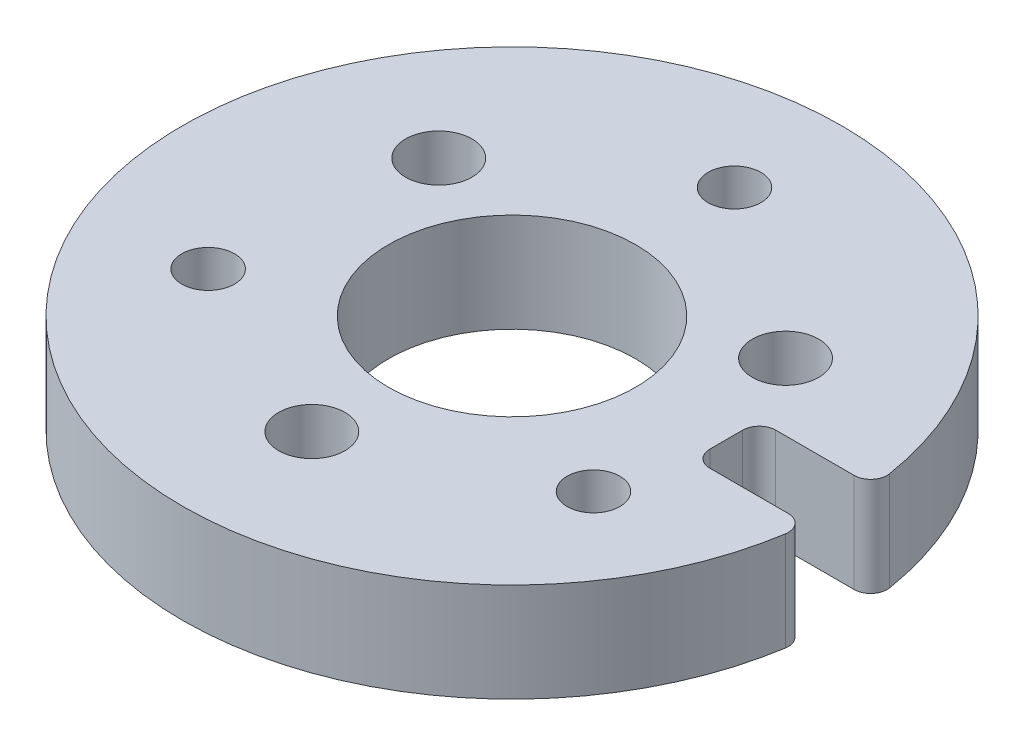
SolidWorks part; units mm, degrees
material "6061 合金"
ref_plane "Front Plane" through (0, 0, 0) normal (0, 0, 1) x (1, 0, 0)
ref_plane "Top Plane" through (0, 0, 0) normal (0, 1, 0) x (1, 0, 0)
ref_plane "Right Plane" through (0, 0, 0) normal (1, 0, 0) x (0, 0, -1)
other "Configuration Table"
sketch "草图1" plane through (0, 0, 0) normal (0, 1, 0) x (1, 0, 0)
  line L0 (0, 0) -> (-10.5222, 6.075) construction
  line L1 (0, 0) -> (-20, 0) construction
  circle A0 centre (0, 0) radius 20
  circle A1 centre (0, 0) radius 13.5 construction
  circle A2 centre (0, 13.5) radius 1.6
  circle A3 centre (11.6913, -6.75) radius 1.6
  circle A4 centre (-11.6913, -6.75) radius 1.6
  circle A5 centre (0, 0) radius 7.5
  circle A6 centre (-10.5222, 6.075) radius 2.015
  circle A7 centre (0, 0) radius 7.5
  circle A8 centre (10.5222, 6.075) radius 2.015
  circle A9 centre (0, 0) radius 7.5
  circle A10 centre (0, -12.15) radius 2.015
  circle A11 centre (0, 0) radius 12.15 construction
  point P22 (0, 0)
  dimension "D1" = 40
  dimension "D2" = 27
  dimension "D3" = 3.2
  dimension "D4" = 15
  dimension "D5" = 4.03
  dimension "D8" = 24.3
  dimension "D6" = 30
  dimension "D9" = 3
  dimension "D7" = 3
extrude "凸台-拉伸1" add sketch "草图1" along normal blind 6 contours A0 A10 A8 A6 A5 A4 A3 A2
sketch "草图2" plane through (0, 6, 0) normal (0, 1, 0) x (1, 0, 0)
  line L0 (0, 0) -> (20, 0) construction
  line L2 (13, 2) -> (27.1782, 2)
  line L3 (13, 2) -> (13, -2)
  line L4 (13, -2) -> (27.1782, -2)
  line L5 (27.1782, 2) -> (27.1782, -2)
  circle A0 centre (0, 0) radius 20 construction
  dimension "D1" = 7
  dimension "D2" = 2
extrude "切除-拉伸1" cut sketch "草图2" against normal blind 10
fillet "圆角1" radius 1 4 edges at (19.8997, 3, 2) (19.8997, 3, -2) (13, 3, 2) (13, 3, -2)
